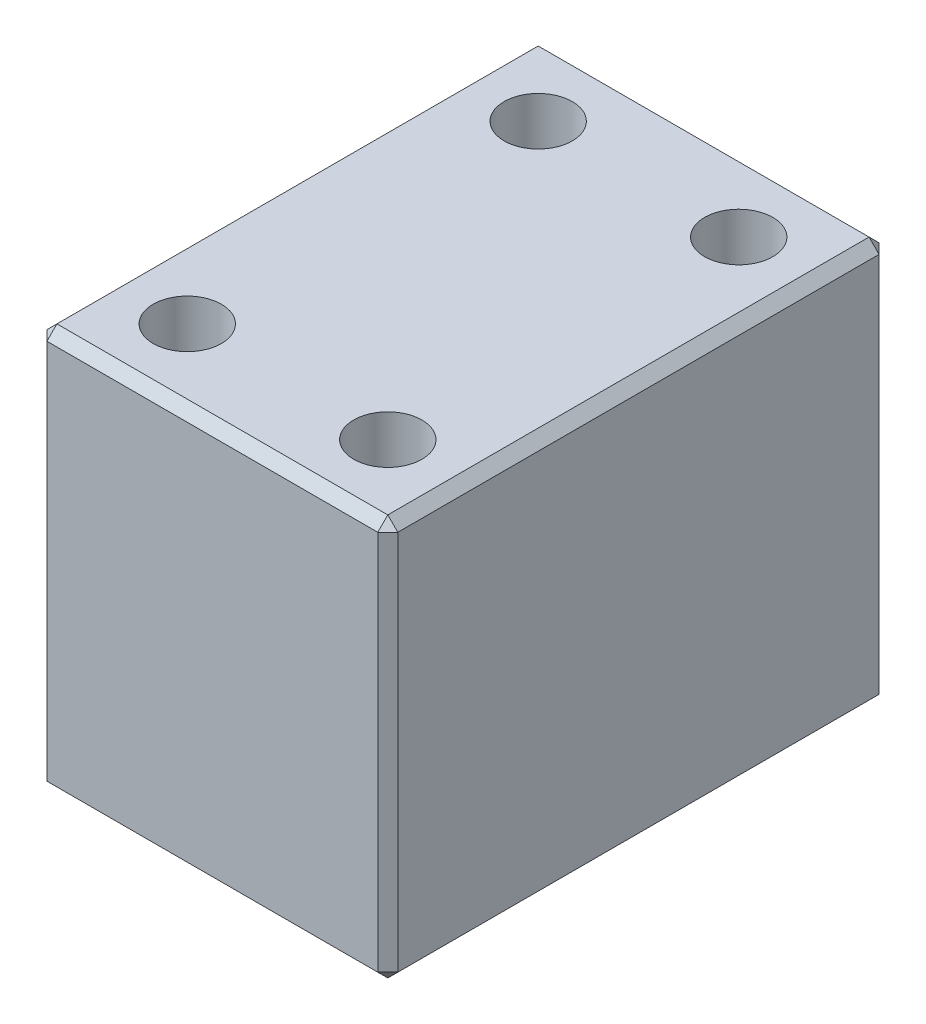
SolidWorks part; units mm, degrees
material "Plain Carbon Steel"
ref_plane "Front Plane" through (0, 0, 0) normal (0, 0, 1) x (1, 0, 0)
ref_plane "Top Plane" through (0, 0, 0) normal (0, 1, 0) x (1, 0, 0)
ref_plane "Right Plane" through (0, 0, 0) normal (1, 0, 0) x (0, 0, -1)
sketch "Sketch1" plane through (0, 0, 0) normal (0, 1, 0) x (1, 0, 0)
  line L1 (-17.5, -25) -> (17.5, -25)
  line L2 (-17.5, -25) -> (-17.5, 25)
  line L3 (-17.5, 25) -> (17.5, 25)
  line L4 (17.5, -25) -> (17.5, 25)
  line L5 (-17.5, -25) -> (17.5, 25) construction
  line L6 (-17.5, 25) -> (17.5, -25) construction
  point P0 (0, 0)
  dimension "D1" = 35
  dimension "D2" = 50
extrude "Boss-Extrude1" add sketch "Sketch1" against normal blind 40
chamfer "Chamfer1" distance 1 angle 45 12 edges at (0, -40, -25) (0, 0, -25) (-17.5, -40, 0) (-17.5, -20, -25) (-17.5, 0, 0) (0, -40, 25) (-17.5, -20, 25) (0, 0, 25) (17.5, -20, -25) (17.5, -40, 0) (17.5, -20, 25) (17.5, 0, 0)
hole_wizard "M8 Tapped Hole1" positions "Sketch4" profile "Sketch3" tap size "M8" standard "ISO"
sketch "Sketch4" plane through (0, 0, 0) normal (0, 1, 0) x (1, 0, 0)
  line L2 (-16.5, 0) -> (16.5, 0) construction
  line L3 (-16.5, 24) -> (-16.5, -24) construction
  line L4 (16.5, -24) -> (16.5, 24) construction
  line L5 (-16.5, 25) -> (16.5, 25) construction
  line L7 (17.5, 24) -> (17.5, -24) construction
  line L9 (-17.5, -24) -> (-17.5, 24) construction
  line L10 (16.5, -25) -> (-16.5, -25) construction
  point P0 (-10, 17.5)
  point P2 (10, -17.5)
  dimension "D1" = 7.5
  dimension "D2" = 7.5
  dimension "D3" = 7.5
  dimension "D4" = 7.5
sketch "Sketch3" plane through (-10, 0, -17.5) normal (1, 0, 0) x (0, 0, 1)
  line L0 (0, 0) -> (0, 21.7929)
  line L1 (0, 21.7929) -> (3.4, 19.75)
  line L2 (3.4, 19.75) -> (3.4, 0)
  line L5 (3.4, 0) -> (0, 0)
  line L10 (0, 21.7929) -> (-3.4, 19.75) construction
  line L11 (0, -6.35) -> (0, 107.95) construction
  dimension "Tap Drill Dia." = 6.8
  dimension "Tap Drill Depth" = 19.75
  dimension "Drill Angle" = 118
cosmetic thread "Hole Thread1"
cosmetic thread "Hole Thread2"
mirror "Mirror1" about plane through (0, 0, 0) normal (0, 0, 1) of "M8 Tapped Hole1"
cosmetic thread "Hole Thread3"
cosmetic thread "Hole Thread4"
